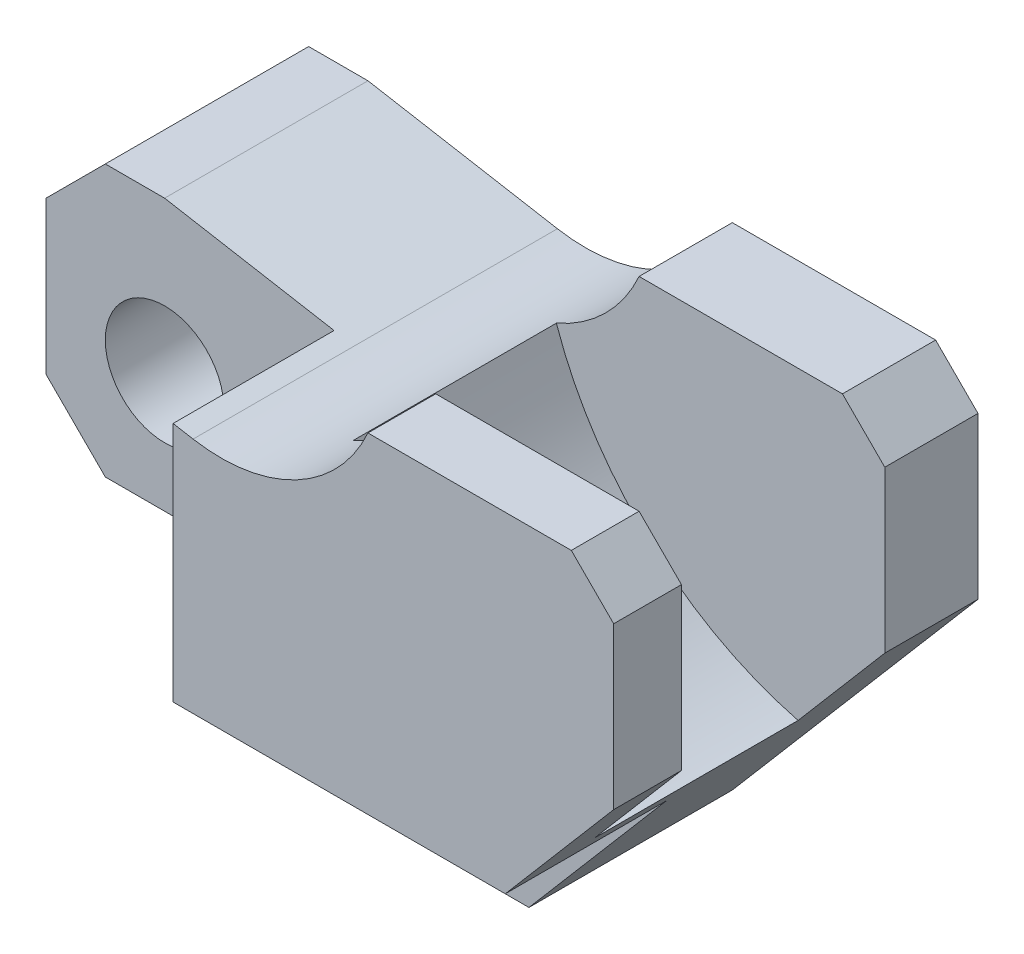
SolidWorks part; units mm, degrees
ref_plane "前基準面" through (0, 0, 0) normal (0, 0, 1) x (1, 0, 0)
ref_plane "上基準面" through (0, 0, 0) normal (0, 1, 0) x (1, 0, 0)
ref_plane "右基準面" through (0, 0, 0) normal (1, 0, 0) x (0, 0, -1)
sketch "草圖2" plane through (0, 0, 0) normal (0, 0, 1) x (1, 0, 0)
  line L0 (0, 0) -> (22.7674, 0) construction
  line L1 (0, 0) -> (0, 19.8285) construction
  line L2 (-14, 11) -> (-14, -7)
  line L3 (-14, -7) -> (-7, -14)
  line L4 (-7, -14) -> (25.5755, -14)
  line L5 (-14, 11) -> (-7, 18)
  line L6 (-7, 18) -> (0, 18)
  line L7 (0, 18) -> (22.3614, 14.0571)
  line L8 (43, 25) -> (67, 25)
  line L9 (67, 25) -> (72, 20)
  line L10 (72, 20) -> (72, 1)
  line L11 (72, 1) -> (43, -33)
  line L12 (43, -33) -> (37.297, -33)
  circle A0 centre (0, 0) radius 7
  arc A1 (22.3614, 14.0571) -> (43, 25) centre (25.6607, 32.7684) ccw
  arc A2 (25.5755, -14) -> (30.5212, -18.2647) centre (25.5755, -19) cw
  arc A3 (30.5212, -18.2647) -> (37.297, -33) centre (59.2059, -14) ccw
  point P2 (-3.5, 18)
  dimension "D1" = 14
  dimension "D10" = 19
  dimension "D11" = 5
  dimension "D12" = 32
  dimension "D13" = 29
  dimension "D18" = 29
  dimension "D2" = 45
  dimension "D3" = 7
  dimension "D4" = 14
  dimension "D5" = 14
  dimension "D6" = 14
  dimension "D7" = 7
  dimension "D8" = 45
  dimension "D9" = 10
  dimension "D14" = 45
  dimension "D15" = 5
  dimension "D16" = 24
  dimension "D17" = 86
  dimension "D19" = 58
  dimension "D20" = 19
  dimension "D21" = 19
  dimension "D22" = 29
extrude "填料-伸長1" add sketch "草圖2" along normal blind 43
sketch "草圖4" plane through (0, 0, 43) normal (0, 0, 1) x (1, 0, 0)
  line L1 (-8.6676, 10.4834) -> (42.611, 10.4834)
  line L2 (-8.6676, 10.4834) -> (-8.6676, -32.0486)
  line L3 (-8.6676, -32.0486) -> (42.611, -32.0486)
  line L4 (42.611, 10.4834) -> (42.611, -32.0486)
sketch "草圖5" plane through (0, 0, 0) normal (0, 1, 0) x (1, 0, 0)
  line L0 (72, -43) -> (72, 0) construction
  line L1 (-14, -24) -> (20, -24)
  line L2 (-14, -24) -> (-14, -43)
  line L3 (-14, -43) -> (20, -43)
  line L4 (20, -24) -> (20, -43)
  line L6 (22.3614, -43) -> (0, -43) construction
  line L9 (-14, -43) -> (-14, 0) construction
  dimension "D1" = 52
  dimension "D2" = 19
extrude "除料-伸長2" cut sketch "草圖5" against normal mid plane 70
sketch "草圖6" plane through (0, 0, 43) normal (0, 0, 1) x (1, 0, 0)
  line L0 (37.297, -33) -> (43, -33) construction
  line L1 (16.0992, -14) -> (78.5978, -14)
  line L2 (16.0992, -14) -> (16.0992, -52.9833)
  line L3 (16.0992, -52.9833) -> (78.5978, -52.9833)
  line L4 (78.5978, -14) -> (78.5978, -52.9833)
  dimension "D1" = 19
extrude "除料-伸長3" cut sketch "草圖6" against normal blind 19
sketch "草圖7" plane through (0, 0, 43) normal (0, 0, 1) x (1, 0, 0)
  line L7 (20, -14) -> (59.2059, -14)
  line L8 (59.2059, -14) -> (72, 1)
  line L9 (72, 1) -> (72, 20)
  line L10 (72, 20) -> (67, 25)
  line L11 (67, 25) -> (43, 25)
  line L12 (22.3614, 14.0571) -> (20, 14.4735)
  line L13 (20, 14.4735) -> (20, -14)
  line L14 (20, -14) -> (59.2059, -14)
  line L15 (59.2059, -14) -> (72, 1)
  line L16 (72, 1) -> (72, 20)
  line L17 (72, 20) -> (67, 25)
  line L18 (67, 25) -> (43, 25)
  line L19 (22.3614, 14.0571) -> (20, 14.4735)
  line L20 (20, 14.4735) -> (20, -14)
  arc A1 (22.3614, 14.0571) -> (43, 25) centre (25.6607, 32.7684) ccw
  arc A2 (22.3614, 14.0571) -> (43, 25) centre (25.6607, 32.7684) ccw
  point P11 (0, 0)
  dimension "D1" = 0
sketch "草圖9" plane through (0, 0, 43) normal (0, 0, 1) x (1, 0, 0)
  line L7 (20, -14) -> (59.2059, -14)
  line L8 (59.2059, -14) -> (72, 1)
  line L9 (72, 1) -> (72, 20)
  line L10 (72, 20) -> (67, 25)
  line L11 (67, 25) -> (43, 25)
  line L12 (22.3614, 14.0571) -> (20, 14.4735)
  line L13 (20, 14.4735) -> (20, -14)
  line L14 (20, -14) -> (59.2059, -14)
  line L15 (59.2059, -14) -> (72, 1)
  line L16 (72, 1) -> (72, 20)
  line L17 (72, 20) -> (67, 25)
  line L18 (67, 25) -> (43, 25)
  line L19 (22.3614, 14.0571) -> (20, 14.4735)
  line L20 (20, 14.4735) -> (20, -14)
  circle A0 centre (72, 28.7019) radius 41
  arc A1 (22.3614, 14.0571) -> (43, 25) centre (25.6607, 32.7684) ccw
  arc A2 (22.3614, 14.0571) -> (43, 25) centre (25.6607, 32.7684) ccw
  point P11 (61.7647, -11)
  point P12 (0, 0)
  line M11 (72, 1) -> (72, 20)
  line M12 (72, 20) -> (67, 25)
  line M13 (67, 25) -> (43, 25)
  arc M14 (43, 25) -> (22.3614, 14.0571) centre (25.6607, 32.7684) cw
  dimension "D2" = 82
  dimension "D3" = 36
  dimension "D1" = 0
extrude "除料-伸長5" cut sketch "草圖9" against normal blind 24 from offset 8 contours A0 L15 M14 M11 M12 M13
